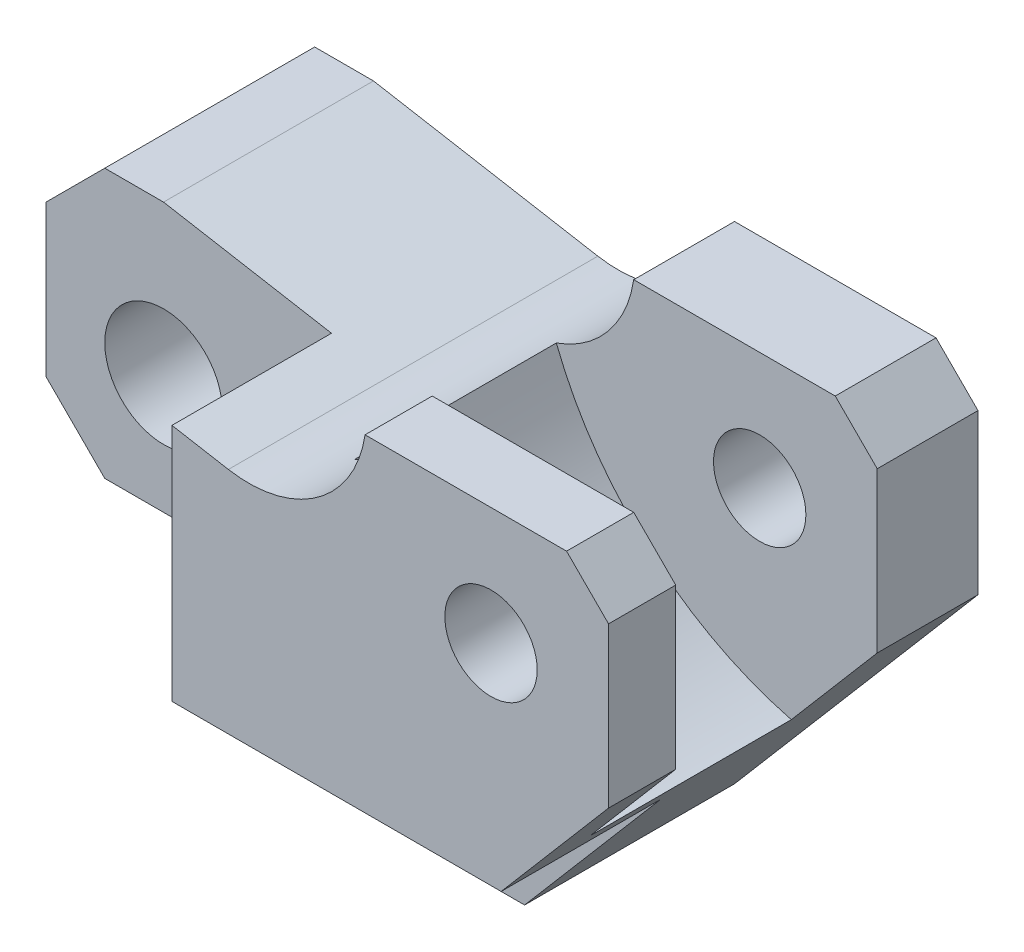
SolidWorks part; units mm, degrees
material "AISI 1020"
ref_plane "Front Plane" through (0, 0, 0) normal (0, 0, 1) x (1, 0, 0)
ref_plane "Top Plane" through (0, 0, 0) normal (0, 1, 0) x (1, 0, 0)
ref_plane "Right Plane" through (0, 0, 0) normal (1, 0, 0) x (0, 0, -1)
other "Center of Mass"
sketch "Sketch1" plane through (0, 0, 0) normal (0, 0, 1) x (1, 0, 0)
  line L0 (-79.9804, 23.3665) -> (-79.9804, 5.3665)
  line L1 (-72.9804, 30.3665) -> (-65.9804, 30.3665)
  line L2 (-72.9804, -1.6335) -> (-40.4049, -1.6335)
  line L3 (-72.9804, 30.3665) -> (-79.9804, 23.3665)
  line L8 (-79.9804, 23.3665) -> (-79.9804, 55.1551) construction
  line L9 (-79.9804, 5.3665) -> (-72.9804, -1.6335)
  line L10 (-79.9804, 5.3665) -> (-79.9804, -51.1023) construction
  line L11 (-65.9804, 30.3665) -> (-39.2569, 25.6544)
  line L12 (-65.9804, 30.3665) -> (-36.6575, 30.3665) construction
  line L13 (-22.9804, 37.3665) -> (1.0196, 37.3665)
  line L14 (1.0196, 37.3665) -> (6.0196, 32.3665)
  line L15 (6.0196, 32.3665) -> (6.0196, 13.3665)
  line L16 (6.0196, 13.3665) -> (-22.9804, -20.6335)
  line L17 (-28.6835, -20.6335) -> (-22.9804, -20.6335)
  circle A0 centre (-65.9804, 12.3665) radius 7
  arc A1 (-39.2569, 25.6544) -> (-22.9804, 37.3665) centre (-36.8258, 39.4417) ccw
  arc A2 (-40.4049, -1.6335) -> (-35.4593, -5.8982) centre (-40.4049, -6.6335) cw
  arc A5 (-35.4593, -5.8982) -> (-28.6835, -20.6335) centre (-6.7746, -1.6335) ccw
  arc A7 (-28.6835, -20.6335) -> (-35.4593, -5.8982) centre (-6.7746, -1.6335) cw
  point P2 (-79.9804, 30.3665)
  point P3 (-79.9804, -1.6335)
  point P20 (6.0196, 37.3665)
  point P21 (0, 0)
  point P23 (0, 0)
  point P25 (-17.9587, -28.9994)
  point P27 (0, 0)
  point P28 (-33.1885, -21.6663)
  point P30 (-40.0524, -6.2613)
  dimension "D7" = 14
  dimension "D10" = 14
  dimension "D15" = 5
  dimension "D16" = 29
  dimension "D4" = 32
  dimension "D3" = 7
  dimension "D1" = 45
  dimension "D2" = 45
  dimension "D6" = 14
  dimension "D8" = 14
  dimension "D9" = 10
  dimension "D11" = 29
  dimension "D12" = 24
  dimension "D14" = 29
  dimension "D17" = 45.2764
  dimension "D18" = 19
  dimension "D19" = 14
  dimension "D20" = 86
  dimension "D21" = 58
  dimension "D22" = 19
extrude "Boss-Extrude1" add sketch "Sketch1" along normal blind 44 contours A2 A5 L17 L16 L15 L14 L13 A1 L11 L1 L3 L0 L9 L2 A0
sketch "Sketch2" plane through (0, 0, 44) normal (0, 0, 1) x (1, 0, 0)
  line L0 (-22.9804, 37.3665) -> (1.0196, 37.3665) construction
  line L1 (6.0196, 32.3665) -> (6.0196, 13.3665) construction
  circle A0 centre (-7.9804, 23.3665) radius 5.5
  dimension "D1" = 11
  dimension "D2" = 14
  dimension "D3" = 14
extrude "Cut-Extrude1" cut sketch "Sketch2" against normal through all
sketch "Sketch3" plane through (0, 0, 44) normal (0, 0, 1) x (1, 0, 0)
  line L0 (-45.9804, 26.84) -> (-45.9804, -1.6335)
  line L4 (6.0196, 32.3665) -> (6.0196, 13.3665) construction
  line L5 (-72.9804, -1.6335) -> (-40.4049, -1.6335) construction
  line L6 (-79.9804, 5.3665) -> (-72.9804, -1.6335) construction
  line L7 (-79.9804, 23.3665) -> (-79.9804, 5.3665) construction
  line L8 (-72.9804, 30.3665) -> (-79.9804, 23.3665) construction
  line L9 (-72.9804, 30.3665) -> (-65.9804, 30.3665) construction
  line L10 (-65.9804, 30.3665) -> (-39.2569, 25.6544) construction
  line L11 (-72.9804, -1.6335) -> (-45.9804, -1.6335)
  line L12 (-79.9804, 5.3665) -> (-72.9804, -1.6335)
  line L13 (-79.9804, 23.3665) -> (-79.9804, 5.3665)
  line L14 (-72.9804, 30.3665) -> (-79.9804, 23.3665)
  line L15 (-72.9804, 30.3665) -> (-65.9804, 30.3665)
  line L16 (-65.9804, 30.3665) -> (-45.9804, 26.84)
  line L17 (-40.4049, -1.6335) -> (-6.7746, -1.6335)
  line L18 (6.0196, 13.3665) -> (-22.9804, -20.6335) construction
  line L20 (-28.6835, -20.6335) -> (-22.9804, -20.6335) construction
  line L21 (-6.7746, -1.6335) -> (-22.9804, -20.6335)
  line L22 (-28.6835, -20.6335) -> (-22.9804, -20.6335)
  arc A0 (-35.4593, -5.8982) -> (-28.6835, -20.6335) centre (-6.7746, -1.6335) ccw construction
  arc A1 (-35.4593, -5.8982) -> (-40.4049, -1.6335) centre (-40.4049, -6.6335) ccw construction
  arc A2 (-35.4593, -5.8982) -> (-28.6835, -20.6335) centre (-6.7746, -1.6335) ccw
  arc A3 (-35.4593, -5.8982) -> (-40.4049, -1.6335) centre (-40.4049, -6.6335) ccw
  dimension "D1" = 52
extrude "Cut-Extrude2" cut sketch "Sketch3" against normal blind 19
ref_plane "Plane1" through (0, 0, 12) normal (0, 0, -1) x (-1, 0, 0)
sketch "Sketch7" plane through (0, 0, 12) normal (0, 0, -1) x (-1, 0, 0)
  line L0 (-6.0196, 13.3665) -> (22.9804, -20.6335) construction
  line L1 (22.9804, 37.3665) -> (-1.0196, 37.3665) construction
  line L2 (-1.0196, 37.3665) -> (-6.0196, 32.3665) construction
  line L3 (-6.0196, 32.3665) -> (-6.0196, 13.3665) construction
  line L4 (-6.0196, 13.3665) -> (4.2157, 1.3665)
  line L5 (22.9804, 37.3665) -> (-1.0196, 37.3665)
  line L6 (-1.0196, 37.3665) -> (-6.0196, 32.3665)
  line L7 (-6.0196, 32.3665) -> (-6.0196, 13.3665)
  line L8 (-6.0196, 32.3665) -> (-6.0196, 49.7702) construction
  arc A0 (4.2157, 1.3665) -> (32.2003, 26.2279) centre (-6.0196, 41.0684) ccw
  arc A1 (22.9804, 37.3665) -> (39.2569, 25.6544) centre (36.8258, 39.4417) ccw construction
  arc A2 (22.9804, 37.3665) -> (32.2003, 26.2279) centre (36.8258, 39.4417) ccw
  point P1 (-6.0196, 41.2598)
  dimension "D1" = 82
  dimension "D2" = 36
extrude "Cut-Extrude3" cut sketch "Sketch7" against normal blind 24
equation "\"A\" = 84mm"
equation "\"B\" = 59mm"
equation "\"C\"= 45mm"
